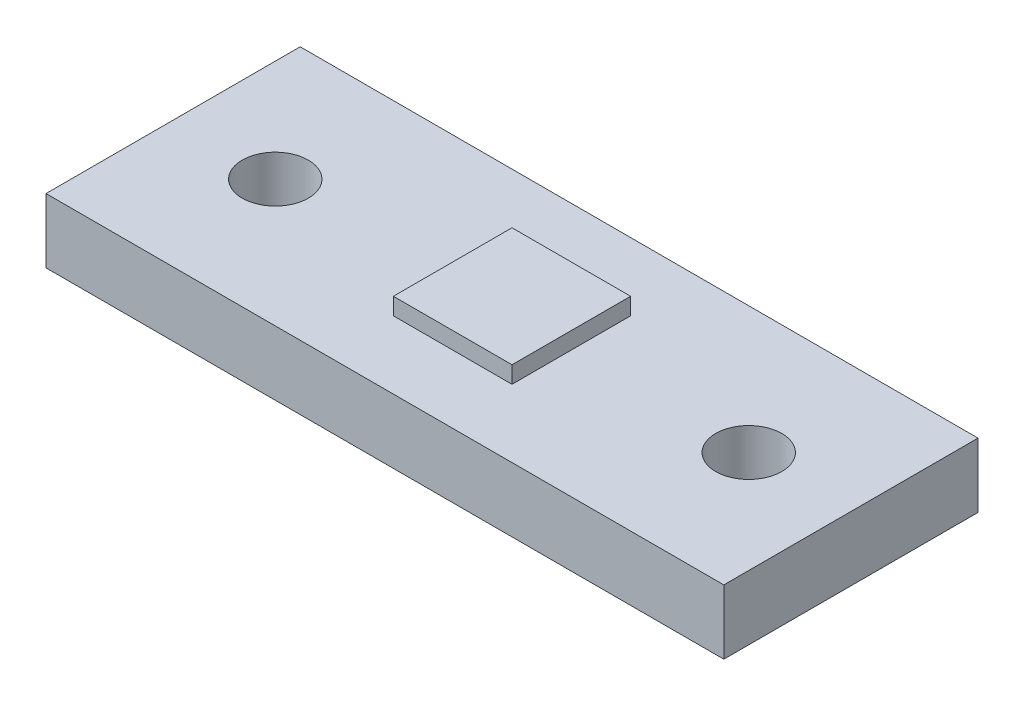
SolidWorks part; units mm, degrees
ref_plane "Front Plane" through (0, 0, 0) normal (0, 0, 1) x (1, 0, 0)
ref_plane "Top Plane" through (0, 0, 0) normal (0, 1, 0) x (1, 0, 0)
ref_plane "Right Plane" through (0, 0, 0) normal (1, 0, 0) x (0, 0, -1)
sketch "Sketch1" plane through (0, 0, 0) normal (0, 1, 0) x (1, 0, 0)
  line L0 (0, 7.5) -> (40, 7.5) construction
  line L1 (0, 0) -> (40, 0)
  line L2 (0, 0) -> (0, 15)
  line L3 (0, 15) -> (40, 15)
  line L4 (40, 0) -> (40, 15)
  line L5 (20, 7.5) -> (20, 15) construction
  circle A0 centre (6.03, 7.5) radius 1.95
  circle A1 centre (33.97, 7.5) radius 1.95
  dimension "D1" = 3.9
  dimension "D2" = 27.94
  dimension "D3" = 40
  dimension "D4" = 15
extrude "Boss-Extrude1" add sketch "Sketch1" along normal blind 3.8
sketch "Sketch3" plane through (0, 3.8, 0) normal (0, 1, 0) x (1, 0, 0)
  line L0 (20, 15) -> (20, 0) construction
  line L1 (40, 15) -> (0, 15) construction
  line L2 (0, 0) -> (40, 0) construction
  line L4 (23.5, 11) -> (16.5, 11)
  line L5 (23.5, 11) -> (23.5, 4)
  line L6 (23.5, 4) -> (16.5, 4)
  line L7 (16.5, 11) -> (16.5, 4)
  line L8 (23.5, 11) -> (16.5, 4) construction
  line L9 (23.5, 4) -> (16.5, 11) construction
  point P6 (20, 7.5)
  dimension "D1" = 7
extrude "Boss-Extrude2" add sketch "Sketch3" along normal blind 1
